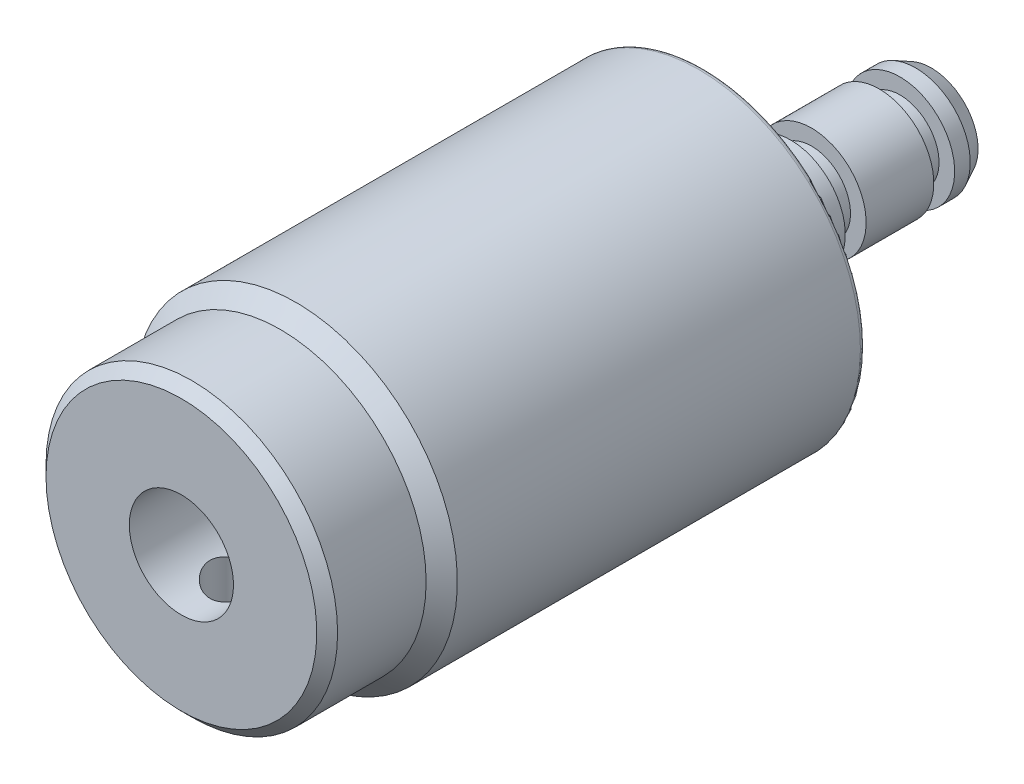
SolidWorks part; units mm, degrees
ref_plane "Top" through (0, 0, 0) normal (0, 0, 1) x (1, 0, 0)
ref_plane "Front" through (0, 0, 0) normal (0, 1, 0) x (1, 0, 0)
ref_plane "Right" through (0, 0, 0) normal (1, 0, 0) x (0, 0, -1)
sketch "Body Sketch" plane through (0, 0, 0) normal (0, 1, 0) x (1, 0, 0)
  line L0 (0, 0) -> (0, -36) construction
  line L1 (2.5, -36) -> (7, -36)
  line L2 (7, -36) -> (7, -31.25)
  line L3 (7, -31.25) -> (7.75, -30.5)
  line L4 (7.75, -30.5) -> (7.75, -10.9)
  line L5 (7.75, -10.9) -> (6, -10.9)
  line L6 (6, -10.9) -> (2.625, -7.75)
  line L7 (2.625, -7.75) -> (2.625, -6.75)
  line L8 (2.625, -6.75) -> (1.875, -6.75)
  line L9 (1.875, -6.75) -> (1.875, -5.75)
  line L10 (1.875, -5.75) -> (2.625, -5.75)
  line L11 (2.625, -5.75) -> (2.625, -2.5)
  line L12 (2.625, -2.5) -> (1.875, -2.5)
  line L13 (1.875, -2.5) -> (1.875, -1.5)
  line L14 (1.875, -1.5) -> (2.625, -1.5)
  line L15 (2.625, -1.5) -> (2.625, -0.75)
  line L16 (2.625, -0.75) -> (2.25, 0)
  line L17 (2.25, 0) -> (1.5, 0)
  line L18 (1.5, 0) -> (1.5, -30.4226)
  line L19 (2.5, -36) -> (2.5, -31)
  line L20 (2.5, -31) -> (1.5, -30.4226)
  dimension "D1" = 7
  dimension "D2" = 4.75
  dimension "D3" = 0.75
  dimension "D4" = 19.6
  dimension "D5" = 0.75
  dimension "D6" = 0.75
  dimension "D7" = 0.75
  dimension "D8" = 1
  dimension "D9" = 2.625
  dimension "D10" = 1.5
  dimension "D11" = 7.75
  dimension "D12" = 36
  dimension "D13" = 1
  dimension "D14" = 3.25
  dimension "D15" = 1
  dimension "D16" = 6
  dimension "D17" = 0.75
  dimension "D18" = 2.5
  dimension "D19" = 5
  dimension "D20" = 120
revolve "Body Revolve" add sketch "Body Sketch" angle 360 about L0
fillet "Outside Bottom Fillet" radius 0.25 1 edges at (-7.75, 0, 10.9)
chamfer "Top Chamfer" distance 0.5 angle 45 1 edges at (-7, 0, 36)
hole_wizard "M3x0.5 Tapped Hole" positions "M3 Position Sketch" profile "M3 Profile Sketch" tap size "M3x0.5" standard "ANSI Metric"
sketch3d "M3 Position Sketch"
  line L2 (0, 0, 0) -> (0, 0, 35.5) construction
  line L3 (0, 0, 30.4226) -> (0, 0, 0) construction
  line L4 (0, 0, 35.5) -> (0, 0, 36) construction
  line L5 (0, 0, 35.5) -> (0, -7, 35.5) construction
  line L7 (0, -7, 35.5) -> (0, -7, 33.375) construction
  circle A0 centre (0, 0, 35.5) radius 7 construction
  point P0 (0, -7, 33.375)
  point P7 (0, 0, 28.5)
  dimension "D1" = 2.125
  dimension "D2" = 7
sketch "M3 Profile Sketch" plane through (0, -7, 33.375) normal (1, 0, 0) x (0, 0, -1)
  line L0 (0, 0) -> (0, 4.5)
  line L1 (0, 4.5) -> (1.25, 4.5)
  line L2 (1.25, 4.5) -> (1.25, 0)
  line L5 (1.25, 0) -> (0, 0)
  line L11 (0, -6.35) -> (0, 107.95) construction
  dimension "Thru Tap Drill Dia." = 2.5
  dimension "Thru Tap Drill Depth" = 4.5
cosmetic thread "M3 Hole Thread" parameters "D2"=3
equation "\"D1@M3 Position Sketch\"=2.375mm-0.25"
